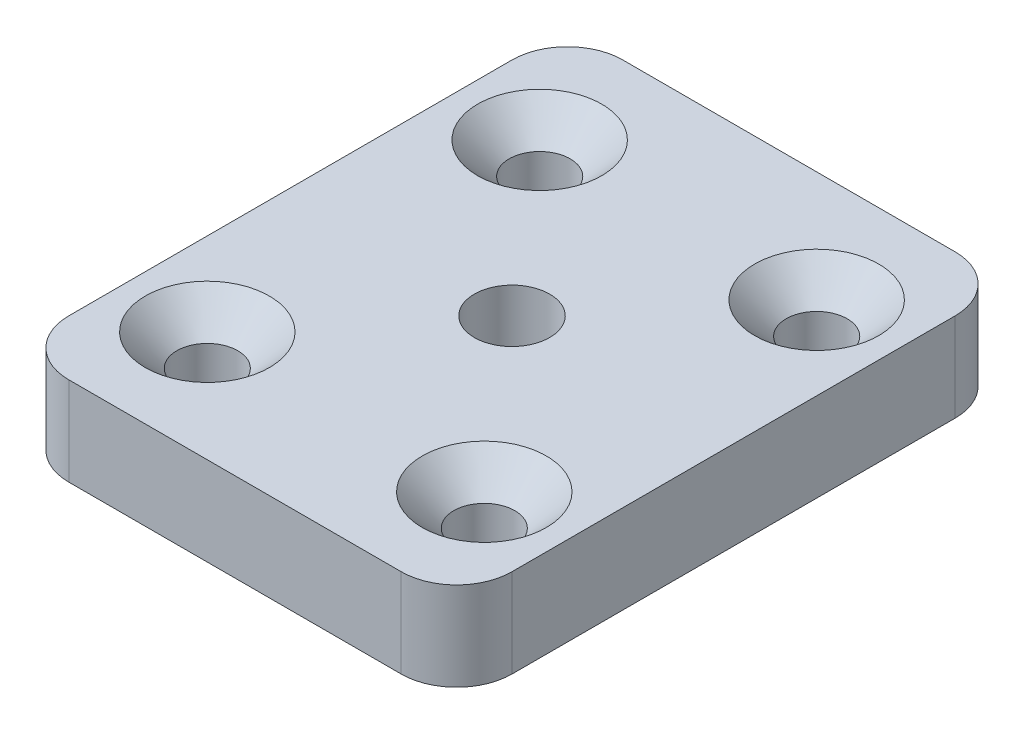
SolidWorks part; units mm, degrees
material "6061-T6 (SS)"
ref_plane "Front Plane" through (0, 0, 0) normal (0, 0, 1) x (1, 0, 0)
ref_plane "Top Plane" through (0, 0, 0) normal (0, 1, 0) x (1, 0, 0)
ref_plane "Right Plane" through (0, 0, 0) normal (1, 0, 0) x (0, 0, -1)
sketch "Sketch1" plane through (0, 0, 0) normal (0, 1, 0) x (1, 0, 0)
  line L1 (-20, -25) -> (20, -25)
  line L2 (-20, -25) -> (-20, 25)
  line L3 (-20, 25) -> (20, 25)
  line L4 (20, -25) -> (20, 25)
  line L5 (-20, -25) -> (20, 25) construction
  line L6 (-20, 25) -> (20, -25) construction
  point P0 (0, 0)
  dimension "D1" = 50
  dimension "D2" = 40
extrude "Boss-Extrude1" add sketch "Sketch1" along normal blind 8
hole_wizard "CSK for M5 Hex Socket Countersunk Cap Screw1" positions "Sketch2" profile "Sketch3" countersink size "M5" standard "ISO" end condition through all
sketch "Sketch2" plane through (0, 8, 0) normal (0, 1, 0) x (1, 0, 0)
  line L1 (12.5, 15) -> (-12.5, 15) construction
  line L2 (12.5, 15) -> (12.5, -15) construction
  line L3 (12.5, -15) -> (-12.5, -15) construction
  line L4 (-12.5, 15) -> (-12.5, -15) construction
  line L5 (12.5, 15) -> (-12.5, -15) construction
  line L6 (12.5, -15) -> (-12.5, 15) construction
  line L8 (20, 25) -> (-20, 25) construction
  point P0 (-12.5, 15)
  point P2 (-12.5, -15)
  point P4 (12.5, -15)
  point P6 (12.5, 15)
  point P59 (0, 0)
  dimension "D1" = 25
  dimension "D2" = 10
sketch "Sketch3" plane through (-12.5, 8, -15) normal (1, 0, 0) x (0, 0, 1)
  line L0 (0, 0) -> (0, 8)
  line L1 (0, 8) -> (2.75, 8)
  line L2 (2.75, 8) -> (2.75, 2.85)
  line L3 (2.75, 2.85) -> (5.6, 0)
  line L5 (5.6, 0) -> (0, 0)
  line L6 (-2.75, 2.85) -> (-5.6, 0) construction
  line L11 (0, -6.35) -> (0, 107.95) construction
  dimension "Thru Hole Dia." = 5.5
  dimension "Thru Hole Depth" = 8
  dimension "Near C'Sink Dia." = 11.2
  dimension "Near C'Sink Angle" = 90
hole_wizard "M8 Tapped Hole1" positions "Sketch4" profile "Sketch5" tap size "M8" standard "ISO" end condition through all
sketch "Sketch4" plane through (0, 8, 0) normal (0, 1, 0) x (1, 0, 0)
  point P0 (0, 0)
sketch "Sketch5" plane through (0, 8, 0) normal (1, 0, 0) x (0, 0, 1)
  line L0 (0, 0) -> (0, 8)
  line L1 (0, 8) -> (3.4, 8)
  line L2 (3.4, 8) -> (3.4, 0)
  line L5 (3.4, 0) -> (0, 0)
  line L11 (0, -6.35) -> (0, 107.95) construction
  dimension "Thru Tap Drill Dia." = 6.8
  dimension "Thru Tap Drill Depth" = 8
cosmetic thread "Hole Thread1" parameters "D2"=8
fillet "Fillet1" radius 5 4 edges at (20, 4, 25) (-20, 4, 25) (-20, 4, -25) (20, 4, -25)
